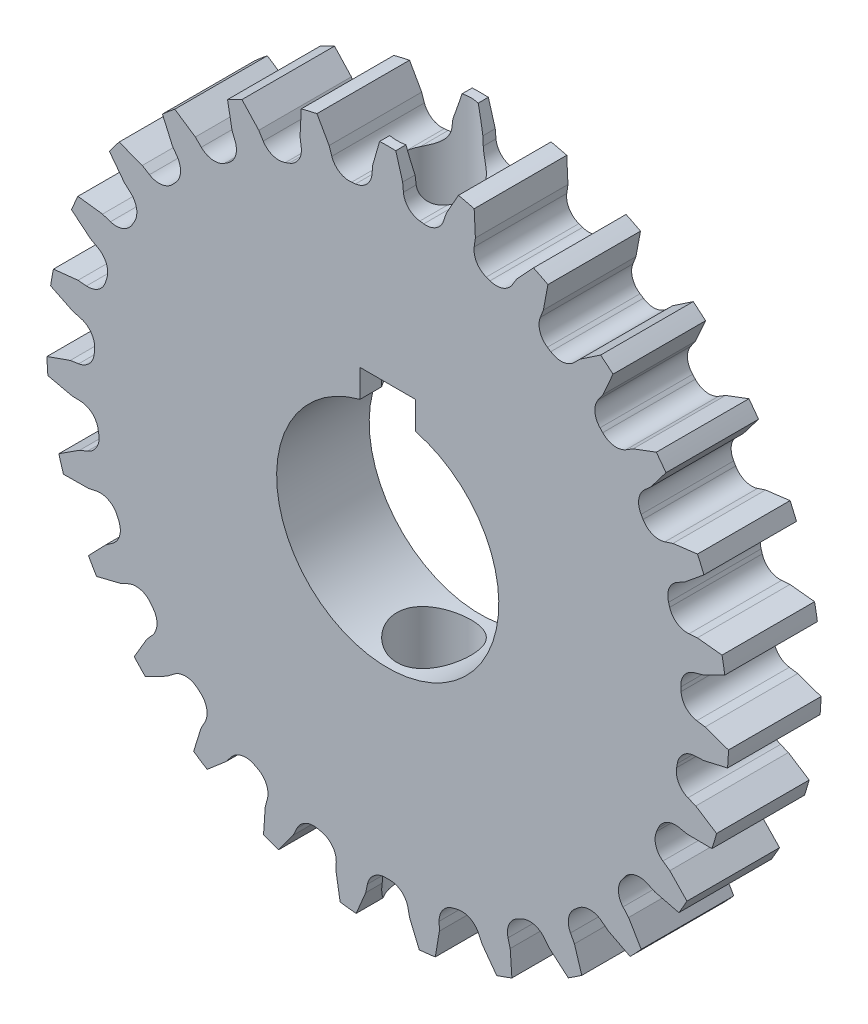
SolidWorks part; units mm, degrees
ref_plane "Front Plane" through (0, 0, 0) normal (0, 0, 1) x (1, 0, 0)
ref_plane "Top Plane" through (0, 0, 0) normal (0, 1, 0) x (1, 0, 0)
ref_plane "Right Plane" through (0, 0, 0) normal (1, 0, 0) x (0, 0, -1)
sketch "Sketch1" plane through (0, 0, 0) normal (0, 0, 1) x (1, 0, 0)
  line L0 (0, -9.2075) -> (0, 9.2075) construction
  line L1 (9.2075, 0) -> (-9.2075, 0) construction
  line L2 (-0.218, 9.2049) -> (-0.4035, 8.563)
  line L3 (-0.4035, 8.563) -> (-0.4628, 7.919)
  line L4 (0.4035, 8.563) -> (0.4628, 7.919)
  line L5 (0.218, 9.2049) -> (0.4035, 8.563)
  circle A0 centre (0, 0) radius 9.2075
  circle A1 centre (0, 0) radius 8.5725 construction
  circle A2 centre (0, 0) radius 7.9325
  point P7 (0, 0)
  point P10 (0, 0)
  dimension "D1" = 18.415
  dimension "D2" = 17.145
  dimension "D3" = 0.64
extrude "Boss-Extrude1" add sketch "Sketch1" along normal mid plane 2.5 contours A2 | A2 L4 L5 A0 L2 L3
pattern_circular "CirPattern1" count 27 over 360 about axis through (0, 0, 0) along (0, 0, 1) of "Boss-Extrude1"
fillet "Fillet1" radius 0.5 2 edges at (-0.4628, 7.919, 0) (0.4628, 7.919, 0)
fillet "Fillet2" radius 0.5 52 edges at (-7.4546, 2.7116, 0) (-7.879, 0.9194, 0) (-7.8787, -0.9225, 0) (-7.4536, -2.7145, 0) (-6.6266, -4.3603, 0) (-5.4425, -5.771, 0) (-3.9649, -6.8705, 0) (-2.2736, -7.5997, 0) (-0.4597, -7.9192, 0) (1.379, -7.8117, 0) (3.1433, -7.2831, 0) (4.7382, -6.3619, 0) (6.0777, -5.0977, 0) (7.0894, -3.5587, 0) (7.719, -1.8278, 0) (7.9325, 0.0016, 0) (7.7183, 1.8309, 0) (7.088, 3.5615, 0) (6.0756, 5.1001, 0) (4.7357, 6.3638, 0) (3.1405, 7.2844, 0) (1.3759, 7.8123, 0) (2.2766, 7.5988, 0) (3.9676, 6.869, 0) (5.4448, 5.7688, 0) (6.6284, 4.3577, 0) (7.4546, 2.7116, 0) (7.879, 0.9194, 0) (7.8787, -0.9225, 0) (7.4536, -2.7145, 0) (6.6266, -4.3603, 0) (5.4425, -5.771, 0) (3.9649, -6.8705, 0) (2.2736, -7.5997, 0) (0.4597, -7.9192, 0) (-1.379, -7.8117, 0) (-3.1433, -7.2831, 0) (-4.7382, -6.3619, 0) (-6.0777, -5.0977, 0) (-7.0894, -3.5587, 0) (-7.719, -1.8278, 0) (-7.9325, 0.0016, 0) (-7.7183, 1.8309, 0) (-7.088, 3.5615, 0) (-6.6284, 4.3577, 0) (-6.0756, 5.1001, 0) (-4.7357, 6.3638, 0) (-5.4448, 5.7688, 0) (-3.9676, 6.869, 0) (-3.1405, 7.2844, 0) (-1.3759, 7.8123, 0) (-2.2766, 7.5988, 0)
sketch "Sketch3" plane through (0, 0, -1.25) normal (0, 0, -1) x (-1, 0, 0)
  line L2 (0.75, 2.9047) -> (0.75, 3.6547)
  line L3 (0.75, 3.6547) -> (-0.75, 3.6547)
  line L4 (-0.75, 2.9047) -> (-0.75, 3.6547)
  line L5 (0, 3) -> (-0.75, 3.6547) construction
  line L6 (0.75, 3.6547) -> (0, 3) construction
  arc A0 (-0.75, 2.9047) -> (0.75, 2.9047) centre (0, 0) ccw
  point P3 (0, 3)
  dimension "D1" = 6
  dimension "D2" = 0.75
  dimension "D3" = 1.5
  dimension "D4" = 0.75
extrude "Cut-Extrude1" cut sketch "Sketch3" against normal through all
sketch "Sketch4" plane through (0, 0, 0) normal (0, 1, 0) x (1, 0, 0)
  circle A0 centre (0, 0) radius 1
  dimension "D1" = 2
extrude "Cut-Extrude2" cut sketch "Sketch4" against normal through all both and the other way through all
